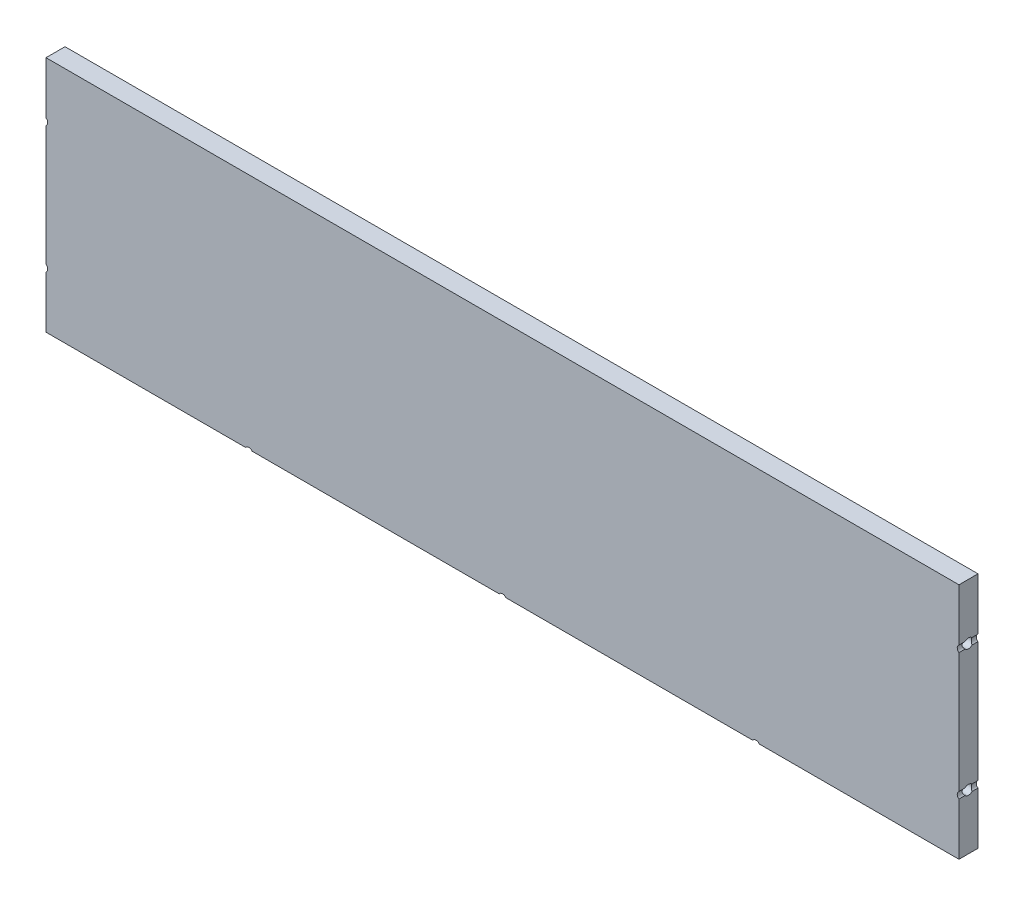
SolidWorks part; units mm, degrees
material "Polypropylene"
ref_plane "正面" through (0, 0, 0) normal (0, 0, 1) x (1, 0, 0)
ref_plane "平面" through (0, 0, 0) normal (0, 1, 0) x (1, 0, 0)
ref_plane "右側面" through (0, 0, 0) normal (1, 0, 0) x (0, 0, -1)
sketch "ｽｹｯﾁ1" plane through (0, 0, 0) normal (0, 1, 0) x (1, 0, 0)
  line L1 (-150, 72.5) -> (150, 72.5)
  line L2 (-150, 72.5) -> (-150, -72.5)
  line L3 (-150, -72.5) -> (150, -72.5)
  line L4 (150, 72.5) -> (150, -72.5)
  line L5 (-150, 72.5) -> (150, -72.5) construction
  line L6 (-150, -72.5) -> (150, 72.5) construction
  point P0 (0, 0)
  dimension "D1" = 300
  dimension "D2" = 145
extrude "ﾎﾞｽ - 押し出し1" add sketch "ｽｹｯﾁ1" along normal blind 81
shell "ｼｪﾙ1" thickness 6
sketch "ｽｹｯﾁ2" plane through (0, 6, 0) normal (0, 1, 0) x (1, 0, 0)
  line L0 (140, 72.5) -> (140, -72.5) construction
  line L1 (150, 72.5) -> (-150, 72.5) construction
  line L2 (-150, -72.5) -> (150, -72.5) construction
  line L3 (140, -72.5) -> (-22.5, -72.5) construction
  line L4 (-22.5, -72.5) -> (-22.5, 72.5) construction
  line L6 (150, -72.5) -> (150, 72.5) construction
  line L7 (-22.5, 0) -> (140, 0) construction
  line L8 (58.75, 72.5) -> (58.75, -72.5) construction
  circle A0 centre (140, 60) radius 2.55
  circle A1 centre (140, -60) radius 2.55
  circle A2 centre (-22.5, -60) radius 2.55
  circle A3 centre (-22.5, 60) radius 2.55
  point P18 (58.75, 0)
  dimension "D3" = 5.1
  dimension "D1" = 162.5
  dimension "D2" = 10
  dimension "D4" = 60
extrude "ｶｯﾄ - 押し出し1" cut sketch "ｽｹｯﾁ2" against normal through all
sketch "ｽｹｯﾁ3" plane through (0, 6, 0) normal (0, 1, 0) x (1, 0, 0)
  circle A0 centre (140, 60) radius 4.25
  circle A1 centre (-22.5, 60) radius 4.25
  circle A2 centre (-22.5, -60) radius 4.25
  circle A3 centre (140, -60) radius 4.25
  dimension "D1" = 8.5
extrude "ｶｯﾄ - 押し出し2" cut sketch "ｽｹｯﾁ3" against normal blind 3
sketch "ｽｹｯﾁ4" plane through (0, 0, 66.5) normal (0, 0, -1) x (-1, 0, 0)
  line L4 (-144, 6) -> (144, 6)
  line L5 (144, 6) -> (144, 81)
  line L6 (144, 81) -> (-144, 81)
  line L7 (-144, 81) -> (-144, 6)
  line L8 (-144, 6) -> (144, 6)
  line L9 (144, 6) -> (144, 81)
  line L10 (144, 81) -> (-144, 81)
  line L11 (-144, 81) -> (-144, 6)
  dimension "D1" = 0
extrude "ｶｯﾄ - 押し出し3" cut sketch "ｽｹｯﾁ4" against normal through all flip side to cut
sketch "ｽｹｯﾁ5" plane through (0, 0, 66.5) normal (0, 0, -1) x (-1, 0, 0)
  line L0 (-144, 43.5) -> (144, 43.5) construction
  line L1 (-144, 81) -> (-144, 6) construction
  line L2 (144, 81) -> (144, 6) construction
  line L4 (144, 6) -> (-144, 6) construction
  line L5 (0, 6) -> (0, 81) construction
  line L6 (144, 81) -> (-144, 81) construction
  circle A0 centre (0, 5.3) radius 1.25
  circle A1 centre (-80, 5.3) radius 1.25
  circle A2 centre (80, 5.3) radius 1.25
  circle A3 centre (-144.7, 63.5) radius 1.25
  circle A4 centre (-144.7, 23.5) radius 1.25
  circle A5 centre (144.7, 23.5) radius 1.25
  circle A6 centre (144.7, 63.5) radius 1.25
  dimension "D1" = 0.7
  dimension "D2" = 2.5
  dimension "D3" = 0.7
  dimension "D4" = 2.5
  dimension "D6" = 0.7
  dimension "D7" = 2.5
  dimension "D5" = 80
  dimension "D8" = 20
extrude "ｶｯﾄ - 押し出し4" cut sketch "ｽｹｯﾁ5" against normal through all
sketch "ｽｹｯﾁ6" plane through (-144, 0, 0) normal (-1, 0, 0) x (0, 0, 1)
  line L0 (69.5, 81) -> (69.5, 6) construction
  line L1 (72.5, 81) -> (66.5, 81) construction
  line L2 (72.5, 6) -> (66.5, 6) construction
  line L3 (66.5, 63.5) -> (72.5, 63.5) construction
  line L4 (66.5, 64.5356) -> (66.5, 62.4644) construction
  line L5 (72.5, 62.4644) -> (72.5, 64.5356) construction
  line L6 (66.5, 23.5) -> (72.5, 23.5) construction
  line L7 (66.5, 24.5356) -> (66.5, 22.4644) construction
  line L8 (72.5, 22.4644) -> (72.5, 24.5356) construction
  circle A0 centre (69.5, 23.5) radius 1.5
  circle A1 centre (69.5, 63.5) radius 1.5
  dimension "D1" = 3
extrude "ｶｯﾄ - 押し出し5" cut sketch "ｽｹｯﾁ6" against normal through all
sketch "ｽｹｯﾁ7" plane through (0, 6, 0) normal (0, -1, 0) x (1, 0, 0)
  line L0 (-144, 69.5) -> (144, 69.5) construction
  line L1 (-144, 72.5) -> (-144, 66.5) construction
  line L2 (144, 72.5) -> (144, 66.5) construction
  line L3 (-80, 72.5) -> (-80, 66.5) construction
  line L4 (-78.9644, 72.5) -> (-81.0356, 72.5) construction
  line L5 (-81.0356, 66.5) -> (-78.9644, 66.5) construction
  line L6 (0, 72.5) -> (0, 66.5) construction
  line L7 (1.0356, 72.5) -> (-1.0356, 72.5) construction
  line L8 (-1.0356, 66.5) -> (1.0356, 66.5) construction
  line L9 (80, 72.5) -> (80, 66.5) construction
  line L10 (81.0356, 72.5) -> (78.9644, 72.5) construction
  line L11 (78.9644, 66.5) -> (81.0356, 66.5) construction
  circle A0 centre (80, 69.5) radius 1.5
  circle A1 centre (0, 69.5) radius 1.5
  circle A2 centre (-80, 69.5) radius 1.5
  dimension "D1" = 3
extrude "ｶｯﾄ - 押し出し6" cut sketch "ｽｹｯﾁ7" against normal blind 10
